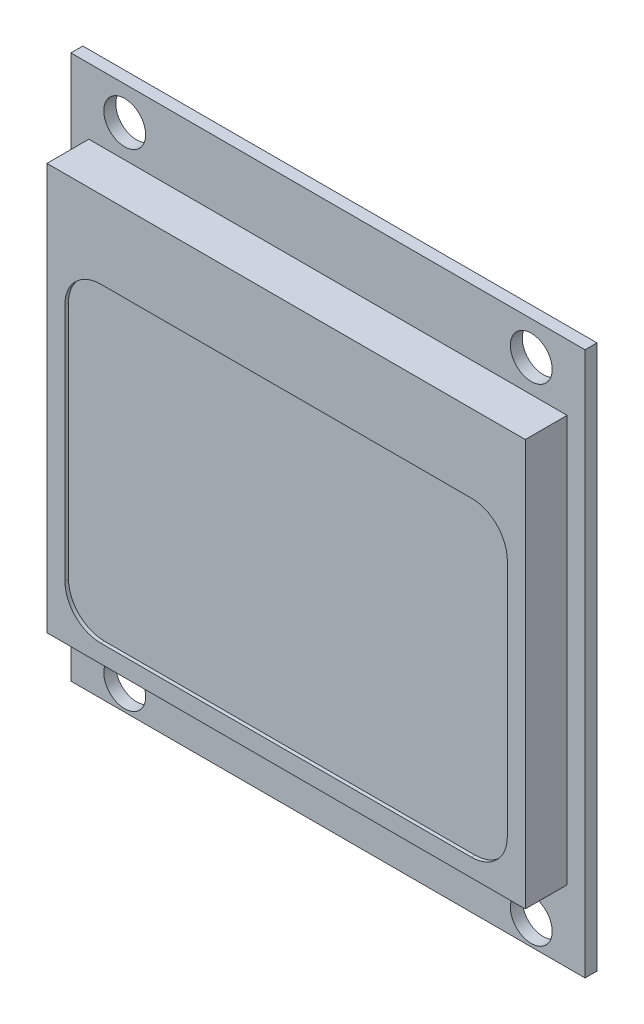
SolidWorks part; units mm, degrees
ref_plane "Front Plane" through (0, 0, 0) normal (0, 0, 1) x (1, 0, 0)
ref_plane "Top Plane" through (0, 0, 0) normal (0, 1, 0) x (1, 0, 0)
ref_plane "Right Plane" through (0, 0, 0) normal (1, 0, 0) x (0, 0, -1)
sketch "Sketch1" plane through (0, 0, 0) normal (0, 0, 1) x (1, 0, 0)
  line L0 (-17, 19.95) -> (-17, -20.75) construction
  line L1 (-21.5, 22.75) -> (21.5, 22.75)
  line L2 (-21.5, 22.75) -> (-21.5, -22.75)
  line L3 (-21.5, -22.75) -> (21.5, -22.75)
  line L4 (21.5, 22.75) -> (21.5, -22.75)
  line L5 (-21.5, 22.75) -> (21.5, -22.75) construction
  line L6 (-21.5, -22.75) -> (21.5, 22.75) construction
  line L7 (-17, -20.75) -> (17, -20.75) construction
  line L8 (17, -20.75) -> (17, 19.95) construction
  line L9 (17, 19.95) -> (-17, 19.95) construction
  circle A0 centre (-17, 19.95) radius 1.75
  circle A1 centre (17, 19.95) radius 1.75
  circle A2 centre (-17, -20.75) radius 1.75
  circle A3 centre (17, -20.75) radius 1.75
  point P0 (0, 0)
  dimension "D4" = 3.5
  dimension "D1" = 43
  dimension "D2" = 45.5
  dimension "D3" = 4.5
  dimension "D5" = 2.8
  dimension "D6" = 2
  dimension "D7" = 4.5
extrude "Boss-Extrude1" add sketch "Sketch1" along normal blind 1
sketch "Sketch2" plane through (0, 0, 1) normal (0, 0, 1) x (1, 0, 0)
  line L0 (0, 0) -> (0, 0.25) construction
  line L1 (-20, 17.25) -> (20, 17.25)
  line L2 (-20, 17.25) -> (-20, -16.75)
  line L3 (-20, -16.75) -> (20, -16.75)
  line L4 (20, 17.25) -> (20, -16.75)
  line L5 (-20, 17.25) -> (20, -16.75) construction
  line L6 (-20, -16.75) -> (20, 17.25) construction
  line L7 (-21.5, -22.75) -> (21.5, -22.75) construction
  point P0 (0, 0.25)
  dimension "D1" = 34
  dimension "D2" = 40
  dimension "D3" = 6
extrude "Boss-Extrude2" add sketch "Sketch2" along normal blind 3.5
sketch "Sketch3" plane through (0, 0, 4.5) normal (0, 0, 1) x (1, 0, 0)
  line L0 (0, 0) -> (0, -2.25) construction
  line L1 (-15.5, 10.75) -> (15.5, 10.75)
  line L2 (-18.5, 7.75) -> (-18.5, -12.25)
  line L3 (-15.5, -15.25) -> (15.5, -15.25)
  line L4 (18.5, 7.75) -> (18.5, -12.25)
  line L5 (-18.5, 10.75) -> (18.5, -15.25) construction
  line L6 (-18.5, -15.25) -> (18.5, 10.75) construction
  line L7 (-20, -16.75) -> (20, -16.75) construction
  arc A0 (-18.5, -12.25) -> (-15.5, -15.25) centre (-15.5, -12.25) ccw
  arc A1 (15.5, -15.25) -> (18.5, -12.25) centre (15.5, -12.25) ccw
  arc A2 (15.5, 10.75) -> (18.5, 7.75) centre (15.5, 7.75) cw
  arc A3 (-15.5, 10.75) -> (-18.5, 7.75) centre (-15.5, 7.75) ccw
  point P0 (0, -2.25)
  dimension "D4" = 3
  dimension "D1" = 37
  dimension "D2" = 26
  dimension "D3" = 1.5
extrude "Cut-Extrude1" cut sketch "Sketch3" against normal blind 0.3
